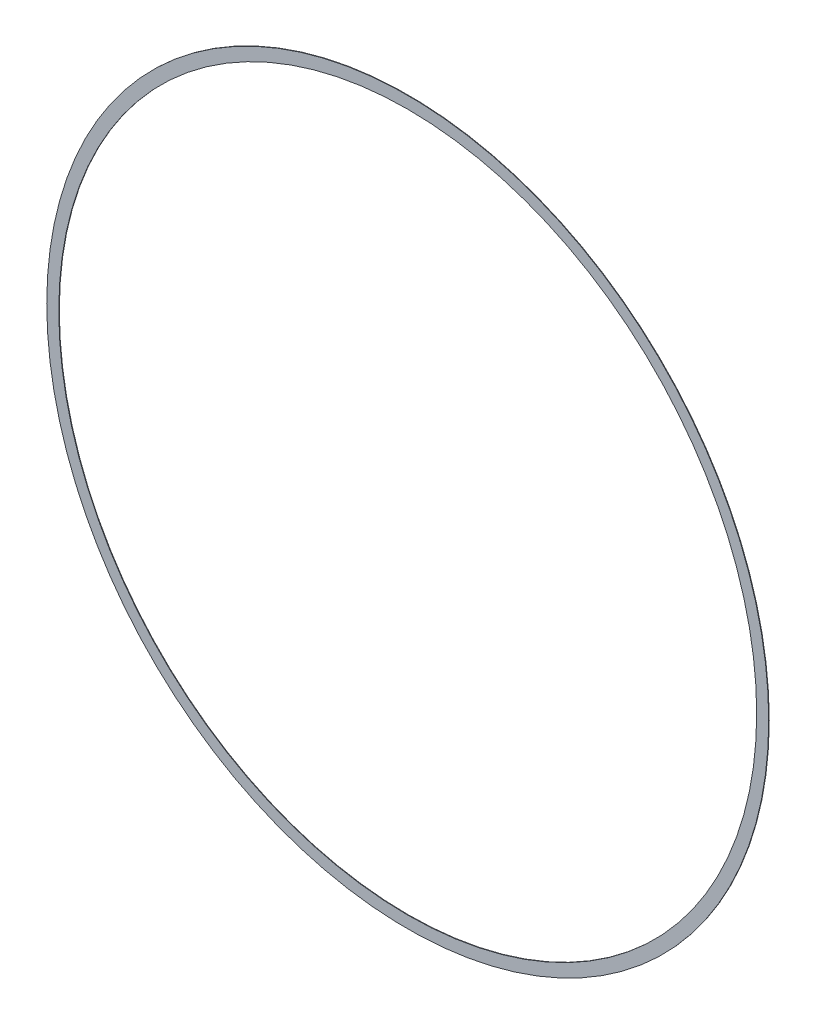
SolidWorks part; units mm, degrees
ref_plane "前视基准面" through (0, 0, 0) normal (0, 0, 1) x (1, 0, 0)
ref_plane "上视基准面" through (0, 0, 0) normal (0, 1, 0) x (1, 0, 0)
ref_plane "右视基准面" through (0, 0, 0) normal (1, 0, 0) x (0, 0, -1)
other "Configuration Table"
sketch "草图1" plane through (0, 0, 0) normal (0, 0, 1) x (1, 0, 0)
  circle A0 centre (0, 0) radius 725
  circle A1 centre (0, 0) radius 750
  dimension "D1" = 1450
  dimension "D2" = 1500
extrude "凸台-拉伸1" add sketch "草图1" along normal blind 1.1
